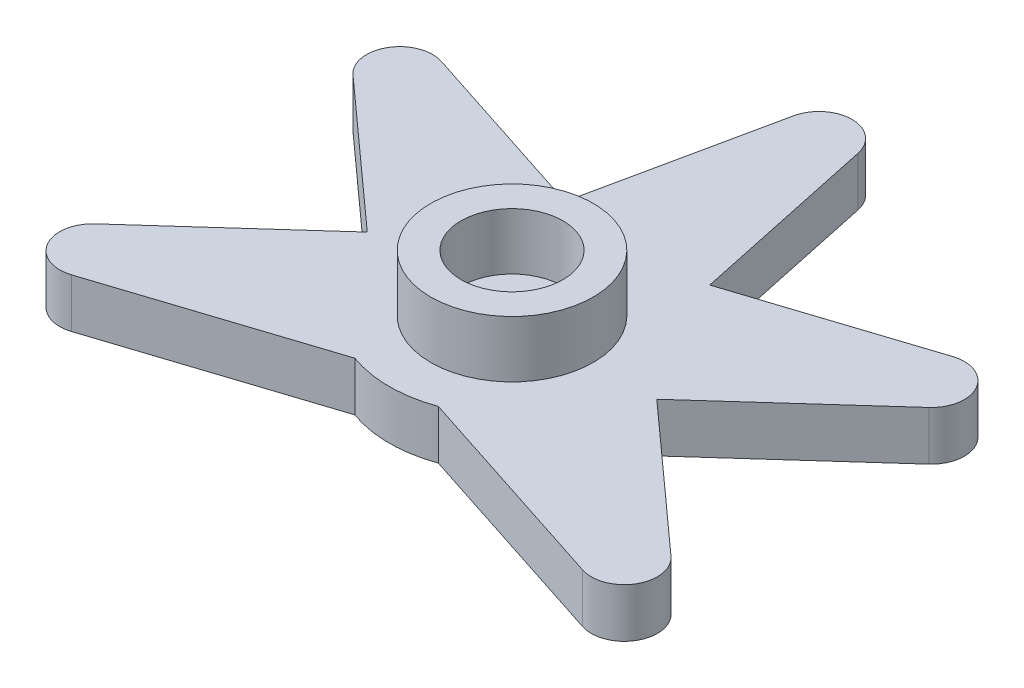
SolidWorks part; units mm, degrees
ref_plane "Front Plane" through (0, 0, 0) normal (0, 0, 1) x (1, 0, 0)
ref_plane "Top Plane" through (0, 0, 0) normal (0, 1, 0) x (1, 0, 0)
ref_plane "Right Plane" through (0, 0, 0) normal (1, 0, 0) x (0, 0, -1)
sketch "Sketch1" plane through (0, 0, 0) normal (0, 1, 0) x (1, 0, 0)
  line L0 (0, 0) -> (0, 18) construction
  line L1 (1.7118, 16.6138) -> (4.1862, 4.9725)
  line L2 (-1.7118, 16.6138) -> (-4.1862, 4.9725)
  line L3 (13.5321, 9.7893) -> (2.2132, 6.1116)
  line L4 (15.2439, 6.8245) -> (6.3994, -1.1391)
  line L5 (15.2439, -6.8245) -> (6.3994, 1.1391)
  line L6 (13.5321, -9.7893) -> (2.2132, -6.1116)
  line L7 (1.7118, -16.6138) -> (4.1862, -4.9725)
  line L8 (-1.7118, -16.6138) -> (-4.1862, -4.9725)
  line L9 (-13.5321, -9.7893) -> (-2.2132, -6.1116)
  line L10 (-15.2439, -6.8245) -> (-6.3994, 1.1391)
  line L11 (-15.2439, 6.8245) -> (-6.3994, -1.1391)
  line L12 (-13.5321, 9.7893) -> (-2.2132, 6.1116)
  circle A0 centre (0, 0) radius 18 construction
  circle A1 centre (0, 0) radius 1.5
  circle A2 centre (0, 0) radius 6.5 construction
  circle A3 centre (0, 16.25) radius 1.75 construction
  arc A4 (-1.7118, 16.6138) -> (1.7118, 16.6138) centre (0, 16.25) cw
  arc A5 (13.5321, 9.7893) -> (15.2439, 6.8245) centre (14.0729, 8.125) cw
  arc A6 (15.2439, -6.8245) -> (13.5321, -9.7893) centre (14.0729, -8.125) cw
  arc A7 (1.7118, -16.6138) -> (-1.7118, -16.6138) centre (0, -16.25) cw
  arc A8 (4.1862, 4.9725) -> (2.2132, 6.1116) centre (0, 0) cw
  arc A9 (-4.1862, -4.9725) -> (-4.1862, 4.9725) centre (0, 0) cw
  arc A10 (4.1862, 4.9725) -> (2.2132, 6.1116) centre (0, 0) cw
  arc A11 (6.3994, -1.1391) -> (6.3994, 1.1391) centre (0, 0) cw
  arc A12 (6.3994, -1.1391) -> (6.3994, 1.1391) centre (0, 0) cw
  arc A13 (2.2132, -6.1116) -> (4.1862, -4.9725) centre (0, 0) cw
  arc A14 (2.2132, -6.1116) -> (4.1862, -4.9725) centre (0, 0) cw
  arc A15 (-4.9725, 4.1862) -> (-4.1862, 4.9725) centre (0, 0) cw
  arc A16 (-13.5321, -9.7893) -> (-15.2439, -6.8245) centre (-14.0729, -8.125) cw
  arc A17 (-15.2439, 6.8245) -> (-13.5321, 9.7893) centre (-14.0729, 8.125) cw
  point P34 (0, 0)
  point P45 (0, 0)
  dimension "D1" = 36
  dimension "D2" = 3
  dimension "D3" = 13
  dimension "D4" = 3.5
  dimension "D5" = 12
  dimension "D6" = 6
extrude "Boss-Extrude1" add sketch "Sketch1" along normal blind 2.6 contours A13 L6 A6 L5 A11 L4 A5 L3 A8 L1 A4 L2 A9 L8 A7 L7 A1 | A17 L11 L10 A8 A14 L2 L12 | L12 A8 L3 L1 A4 L2 | L1 A8 L5 L4 A5 L3 | L4 A8 L7 L6 A6 L5 | A16 L9 L8 A8 L11 L10 | L5 A8 L4 | L7 A8 L6 | L9 A8 L8 | L11 A8 L10 | L2 A8 L12 | L3 A11 L1
sketch "Sketch2" plane through (0, 2.6, 0) normal (0, 1, 0) x (1, 0, 0)
  circle A0 centre (0, 0) radius 4.3
  circle A1 centre (0, 0) radius 2.7
  dimension "D1" = 8.6
  dimension "D2" = 1.6
extrude "Boss-Extrude2" add sketch "Sketch2" along normal blind 3
